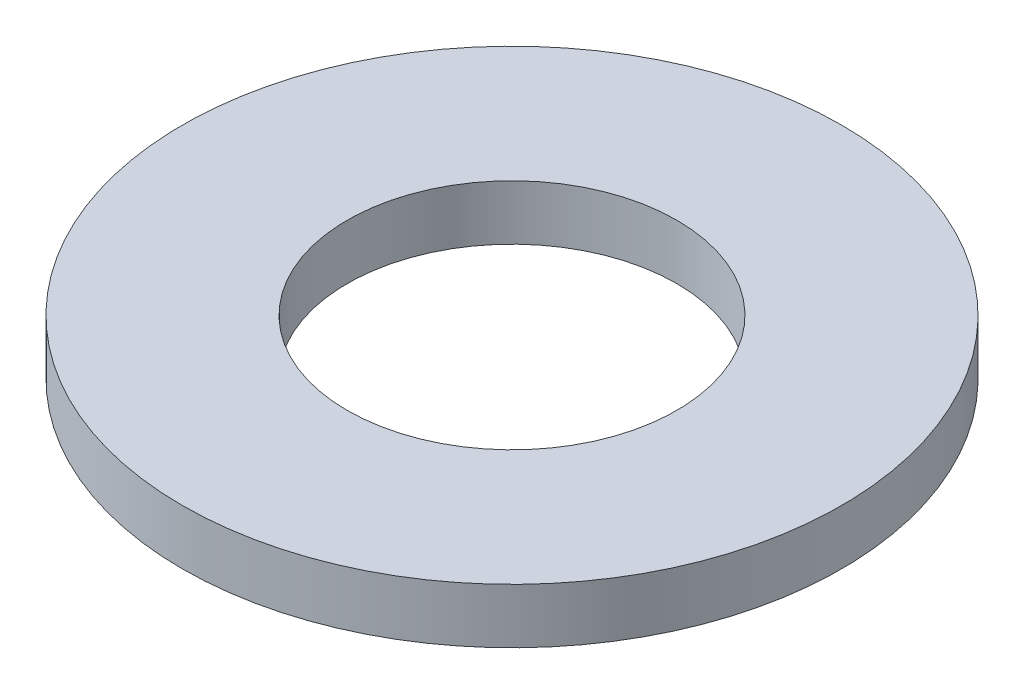
SolidWorks part; units mm, degrees
ref_plane "Front" through (0, 0, 0) normal (0, 0, 1) x (1, 0, 0)
ref_plane "Top" through (0, 0, 0) normal (0, 1, 0) x (1, 0, 0)
ref_plane "Right" through (0, 0, 0) normal (1, 0, 0) x (0, 0, -1)
sketch "Sketch1" plane through (0, 0, 0) normal (0, 1, 0) x (1, 0, 0)
  circle A0 centre (0, 0) radius 7.62
  circle A1 centre (0, 0) radius 15.24
  dimension "D1" = 30.48
  dimension "D2" = 15.24
extrude "Boss-Extrude1" add sketch "Sketch1" along normal blind 2.54 contours A1 | A0
